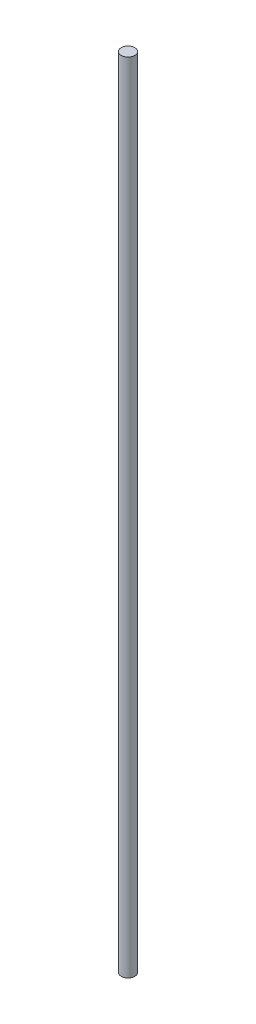
SolidWorks part; units mm, degrees
ref_plane "Спереди" through (0, 0, 0) normal (0, 0, 1) x (1, 0, 0)
ref_plane "Сверху" through (0, 0, 0) normal (0, 1, 0) x (1, 0, 0)
ref_plane "Справа" through (0, 0, 0) normal (1, 0, 0) x (0, 0, -1)
sketch "Эскиз2" plane through (0, 0, 0) normal (0, 0, 1) x (1, 0, 0)
  line L5 (-2.5, 147) -> (0, 147)
  line L6 (-2.5, 147) -> (-2.5, -147)
  line L7 (-2.5, -147) -> (0, -147)
  line L8 (0, 147) -> (0, -147)
  line L9 (-2.5, 147) -> (0, -147) construction
  line L10 (-2.5, -147) -> (0, 147) construction
  point P0 (-1.25, 0)
  point P5 (0, 0)
  dimension "D1" = 2.5
  dimension "D2" = 294
revolve "Повернуть1" add sketch "Эскиз2" angle 360 about L6
equation "\"Ширина груза\"= 160"
equation "\"Глубина груза\"= 240"
equation "\"Высота груза\"= 160"
equation "\"Ширина ячейки\"= \"Ширина груза\" + 10"
equation "\"Глубина ячейки\"= \"Глубина груза\" + 10"
equation "\"Высота ячейки\"= \"Высота груза\" + 10 + 13"
equation "\"Колво ячеек ширина\"= 2"
equation "\"Колво ячеек высота\"= 2"
equation "\"Толщина стенки\" = \"Толщина тонких панелей\""
equation "\"Крепление дверцы\"= 5 "
equation "\"Ширина рейки\"= \"Толщина шестерни\""
equation "\"Высота рейки\"= 20"
equation "\"Высота пола\" = 2*\"Толщина тонких панелей\""
equation "\"Колво полозьев\"= 5"
equation "\"Отступ рейки\"= 20"
equation "\"Глубина каретки\"= \"Глубина ячейки\" + 30 + \"Мотор Y высота корпуса\" + 20"
equation "\"Длинна рейки\" = (\"Ширина ячейки\"+\"Толщина вертикальных стенок\"+\"Крепление дверцы\")*\"Колво ячеек ширина\"+\"Ширина ячейки выгрузки\"*\"Колво выгрузки\"+\"Толщина вертикальных стенок\"+2*\"Отступ крепления мотора фиксации\"-\"Крепление дверцы\"*\"Колво ячеек ширина\""
equation "\"Отступ шпильки\"= 26"
equation "\"Диаметр шпильки\"= 5"
equation "\"Длинна шпильки\" = (\"Высота ячейки\"+\"Толщина горизонтальных плит\"+\"Высота пола\")*\"Колво ячеек высота\"+2*(\"Толщина горизонтальных плит\"+\"Отступ рейки\")"
equation "\"D1@Эскиз2\"= \"Диаметр шпильки\" / 2"
equation "\"D2@Эскиз2\" = \"Глубина каретки\" - \"Мотор Y высота корпуса\" - \"Толщина стенки\""
equation "\"Ширина пластины\"= 50  "
equation "\"Высота зона выгрузки\"= \"Высота ячейки\" * 2 + \"Толщина стенки\" * 2"
equation "\"Колво выгрузки\"= 1"
equation "\"Отступ крепления мотора фиксации\" = (\"Ширина пластины\"+20-\"Толщина вертикальных стенок\")/2"
equation "\"Мотор X ширина корпуса\"= 42.3"
equation "\"Мотор X высота корпуса\"= 42.3"
equation "\"Мотор X длина корпуса\"= 40"
equation "\"Мотор X вылет вала\"= 19.8"
equation "\"Мотор Y ширина корпуса\"= 42.3"
equation "\"Мотор Y высота корпуса\"= 42.3"
equation "\"Мотор Y длина корпуса\"= 48"
equation "\"Мотор Y вылет вала\"= 30"
equation "\"Мотор Z ширина корпуса\"= 42"
equation "\"Мотор Z высота корпуса\"= 42"
equation "\"Мотор Z длина корпуса\"= 40"
equation "\"Мотор Z вылет вала\"= 23"
equation "\"Мотор диаметр вала ПРЕДВ\"= 5"
equation "\"Мотор шаг крепления ПРЕДВ\"= 31"
equation "\"Мотор диаметр отверстий ПРЕДВ\"= 3"
equation "\"Мотор глубина отверстий ПРЕДВ\"= 4.5"
equation "\"Мотор диаметр буртика ПРЕДВ\"= 22"
equation "\"Мотор высота буртика ПРЕДВ\"= 2"
equation "\"Мотор диаметр шкива ПРЕДВ\"= 16"
equation "\"Мотор длина шкива ПРЕДВ\"= 12"
equation "\"Мотор отступ шкива ПРЕДВ\"= 5"
equation "\"Мотор X шаг градусов\"= 1.8"
equation "\"Мотор X ток А\"= 1.5"
equation "\"Мотор X сопротивление Ом\"= 1.3"
equation "\"Мотор X индуктивность мГн\"= 2"
equation "\"Мотор Y шаг градусов\"= 1.8"
equation "\"Мотор Y ток А\"= 2.2"
equation "\"Мотор Y сопротивление Ом\"= 0.9"
equation "\"Мотор Y индуктивность мГн\"= 2"
equation "\"Мотор Z шаг градусов\"= 1.8"
equation "\"Мотор Z ток А\"= 1"
equation "\"Мотор Z сопротивление Ом\"= 4"
equation "\"Мотор Z индуктивность мГн\"= 8"
equation "\"Мотор Y диаметр ротора\"= 25.78"
equation "\"Ширина ячейки выгрузки\" = \"Ширина ячейки\"+\"Толщина вертикальных стенок\"+2*\"Отступ крепления мотора фиксации\""
equation "\"Толщина тонких панелей\" = 6"
equation "\"Толщина вертикальных стенок\" = 6"
equation "\"Толщина горизонтальных плит\" = 6"
equation "\"Базовая высота корпуса\"= (\"Высота ячейки\"+\"Толщина тонких панелей\"+\"Высота пола\")*\"Колво ячеек высота\"+6*\"Толщина тонких панелей\"+\"Мотор X ширина корпуса\"+\"Мотор Y ширина корпуса\"+75"
equation "\"Высота корпуса\"= (\"Высота ячейки\"+\"Толщина горизонтальных плит\"+\"Высота пола\")*\"Колво ячеек высота\"+2*\"Толщина горизонтальных плит\"+4*\"Толщина тонких панелей\"+\"Мотор X ширина корпуса\"+\"Мотор Y ширина корпуса\"+75"
equation "\"Смещение центра корпуса\"= (\"Высота корпуса\"-\"Базовая высота корпуса\")/2-(\"Толщина горизонтальных плит\"-\"Толщина тонких панелей\")"
equation "\"Отметка пола\"= -\"Базовая высота корпуса\"/2+\"Толщина тонких панелей\""
equation "\"Отметка потолка\"= \"Отметка пола\"+\"Высота корпуса\"-2*\"Толщина горизонтальных плит\""
equation "\"Отметка верхней полки\"= \"Отметка потолка\"-(28+\"Толщина тонких панелей\")-\"Высота ячейки\"-\"Высота пола\""
equation "\"Отметка нижней полки\"= \"Отметка верхней полки\"-\"Высота ячейки\"-\"Высота пола\"-\"Толщина горизонтальных плит\""
equation "\"Толщина шестерни\"= 10"
